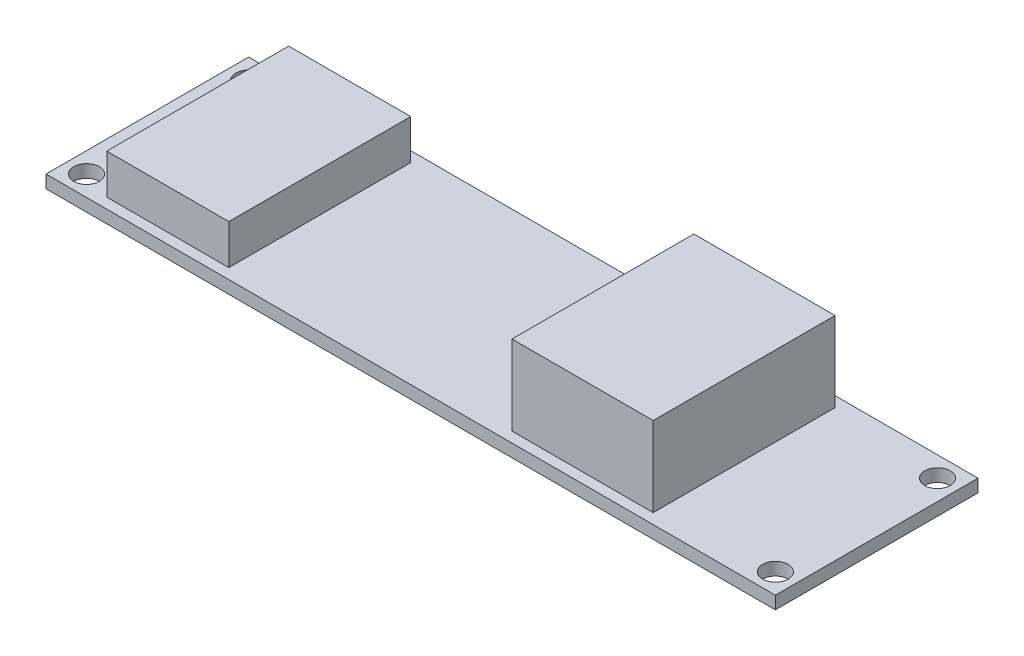
SolidWorks part; units mm, degrees
ref_plane "前视基准面" through (0, 0, 0) normal (0, 0, 1) x (1, 0, 0)
ref_plane "上视基准面" through (0, 0, 0) normal (0, 1, 0) x (1, 0, 0)
ref_plane "右视基准面" through (0, 0, 0) normal (1, 0, 0) x (0, 0, -1)
sketch "草图1" plane through (0, 0, 0) normal (0, 1, 0) x (1, 0, 0)
  line L0 (-13.1829, 0) -> (11.7441, 0) construction
  line L1 (-45.72, 12.7) -> (45.72, 12.7)
  line L2 (-45.72, 12.7) -> (-45.72, -12.7)
  line L3 (-45.72, -12.7) -> (45.72, -12.7)
  line L4 (45.72, 12.7) -> (45.72, -12.7)
  line L5 (-45.72, 12.7) -> (45.72, -12.7) construction
  line L6 (-45.72, -12.7) -> (45.72, 12.7) construction
  line L7 (0, 5.6071) -> (0, -5.463) construction
  circle A0 centre (-43.18, 10.16) radius 1.6
  circle A1 centre (43.18, 10.16) radius 1.6
  circle A2 centre (43.18, -10.16) radius 1.6
  circle A3 centre (-43.18, -10.16) radius 1.6
  point P0 (0, 0)
  dimension "D5" = 3.2
  dimension "D1" = 91.44
  dimension "D2" = 25.4
  dimension "D3" = 43.18
  dimension "D4" = 10.16
extrude "凸台-拉伸1" add sketch "草图1" along normal blind 1.6
sketch "草图2" plane through (0, 1.6, 0) normal (0, 1, 0) x (1, 0, 0)
  line L1 (-39.4, 11.4) -> (-24.1, 11.4)
  line L2 (-39.4, 11.4) -> (-39.4, -11.4)
  line L3 (-39.4, -11.4) -> (-24.1, -11.4)
  line L4 (-24.1, 11.4) -> (-24.1, -11.4)
  dimension "D1" = 39.4
  dimension "D2" = 24.1
  dimension "D3" = 11.4
  dimension "D4" = 11.4
extrude "凸台-拉伸2" add sketch "草图2" along normal blind 5
sketch "草图3" plane through (0, 1.6, 0) normal (0, 1, 0) x (1, 0, 0)
  line L1 (11.4, 11.4) -> (29.1, 11.4)
  line L2 (11.4, 11.4) -> (11.4, -11.4)
  line L3 (11.4, -11.4) -> (29.1, -11.4)
  line L4 (29.1, 11.4) -> (29.1, -11.4)
  dimension "D1" = 11.4
  dimension "D2" = 11.4
  dimension "D3" = 11.4
  dimension "D4" = 29.1
extrude "凸台-拉伸3" add sketch "草图3" along normal blind 10
